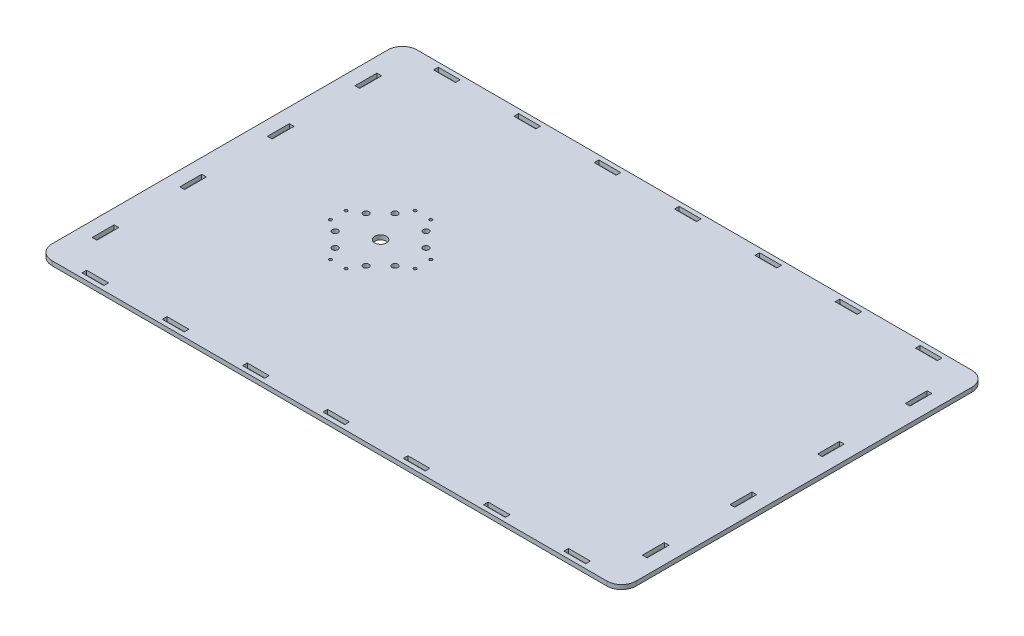
SolidWorks part; units mm, degrees
ref_plane "Front Plane" through (0, 0, 0) normal (0, 0, 1) x (1, 0, 0)
ref_plane "Top Plane" through (0, 0, 0) normal (0, 1, 0) x (1, 0, 0)
ref_plane "Right Plane" through (0, 0, 0) normal (1, 0, 0) x (0, 0, -1)
sketch "Sketch1" plane through (0, 0, 0) normal (0, 1, 0) x (1, 0, 0)
  line L0 (82.5, 3) -> (82.5, 6.2)
  line L1 (0, 0) -> (400, 0)
  line L2 (0, 0) -> (0, 250)
  line L3 (0, 250) -> (400, 250)
  line L4 (400, 0) -> (400, 250)
  line L5 (27.5, 3) -> (42.5, 3)
  line L6 (27.5, 3) -> (27.5, 6.2)
  line L7 (27.5, 6.2) -> (42.5, 6.2)
  line L8 (42.5, 3) -> (42.5, 6.2)
  line L9 (82.5, 3) -> (97.5, 3)
  line L10 (97.5, 3) -> (97.5, 6.2)
  line L11 (82.5, 6.2) -> (97.5, 6.2)
  line L12 (137.5, 3) -> (137.5, 6.2)
  line L13 (137.5, 3) -> (152.5, 3)
  line L14 (152.5, 3) -> (152.5, 6.2)
  line L15 (137.5, 6.2) -> (152.5, 6.2)
  line L16 (192.5, 3) -> (192.5, 6.2)
  line L17 (192.5, 3) -> (207.5, 3)
  line L18 (207.5, 3) -> (207.5, 6.2)
  line L19 (192.5, 6.2) -> (207.5, 6.2)
  line L20 (247.5, 3) -> (247.5, 6.2)
  line L21 (247.5, 3) -> (262.5, 3)
  line L22 (262.5, 3) -> (262.5, 6.2)
  line L23 (247.5, 6.2) -> (262.5, 6.2)
  line L24 (302.5, 3) -> (302.5, 6.2)
  line L25 (302.5, 3) -> (317.5, 3)
  line L26 (317.5, 3) -> (317.5, 6.2)
  line L27 (302.5, 6.2) -> (317.5, 6.2)
  line L28 (357.5, 3) -> (357.5, 6.2)
  line L29 (357.5, 3) -> (372.5, 3)
  line L30 (372.5, 3) -> (372.5, 6.2)
  line L31 (357.5, 6.2) -> (372.5, 6.2)
  line L32 (0, 125) -> (400, 125) construction
  line L33 (357.5, 247) -> (372.5, 247)
  line L34 (372.5, 247) -> (372.5, 243.8)
  line L35 (357.5, 243.8) -> (372.5, 243.8)
  line L36 (357.5, 247) -> (357.5, 243.8)
  line L37 (302.5, 247) -> (317.5, 247)
  line L38 (317.5, 247) -> (317.5, 243.8)
  line L39 (302.5, 243.8) -> (317.5, 243.8)
  line L40 (302.5, 247) -> (302.5, 243.8)
  line L41 (247.5, 247) -> (262.5, 247)
  line L42 (262.5, 247) -> (262.5, 243.8)
  line L43 (247.5, 243.8) -> (262.5, 243.8)
  line L44 (247.5, 247) -> (247.5, 243.8)
  line L45 (192.5, 247) -> (207.5, 247)
  line L46 (207.5, 247) -> (207.5, 243.8)
  line L47 (192.5, 243.8) -> (207.5, 243.8)
  line L48 (192.5, 247) -> (192.5, 243.8)
  line L49 (27.5, 243.8) -> (42.5, 243.8)
  line L50 (42.5, 247) -> (42.5, 243.8)
  line L51 (27.5, 247) -> (42.5, 247)
  line L52 (27.5, 247) -> (27.5, 243.8)
  line L53 (82.5, 247) -> (97.5, 247)
  line L54 (97.5, 247) -> (97.5, 243.8)
  line L55 (82.5, 243.8) -> (97.5, 243.8)
  line L56 (82.5, 247) -> (82.5, 243.8)
  line L57 (137.5, 247) -> (152.5, 247)
  line L58 (152.5, 247) -> (152.5, 243.8)
  line L59 (137.5, 243.8) -> (152.5, 243.8)
  line L60 (137.5, 247) -> (137.5, 243.8)
  line L61 (200, 0) -> (200, 250) construction
  line L62 (10, 102.5) -> (10, 87.5)
  line L63 (10, 42.5) -> (13.2, 42.5)
  line L64 (10, 42.5) -> (10, 27.5)
  line L65 (10, 27.5) -> (13.2, 27.5)
  line L66 (13.2, 42.5) -> (13.2, 27.5)
  line L67 (10, 102.5) -> (13.2, 102.5)
  line L68 (13.2, 102.5) -> (13.2, 87.5)
  line L69 (10, 87.5) -> (13.2, 87.5)
  line L70 (10, 162.5) -> (10, 147.5)
  line L71 (10, 162.5) -> (13.2, 162.5)
  line L72 (13.2, 162.5) -> (13.2, 147.5)
  line L73 (10, 147.5) -> (13.2, 147.5)
  line L74 (10, 222.5) -> (10, 207.5)
  line L75 (10, 222.5) -> (13.2, 222.5)
  line L76 (13.2, 222.5) -> (13.2, 207.5)
  line L77 (10, 207.5) -> (13.2, 207.5)
  line L78 (390, 27.5) -> (386.8, 27.5)
  line L79 (386.8, 42.5) -> (386.8, 27.5)
  line L80 (390, 42.5) -> (386.8, 42.5)
  line L81 (390, 42.5) -> (390, 27.5)
  line L82 (390, 102.5) -> (386.8, 102.5)
  line L83 (386.8, 102.5) -> (386.8, 87.5)
  line L84 (390, 87.5) -> (386.8, 87.5)
  line L85 (390, 102.5) -> (390, 87.5)
  line L86 (390, 162.5) -> (386.8, 162.5)
  line L87 (386.8, 162.5) -> (386.8, 147.5)
  line L88 (390, 147.5) -> (386.8, 147.5)
  line L89 (390, 162.5) -> (390, 147.5)
  line L90 (390, 222.5) -> (386.8, 222.5)
  line L91 (386.8, 222.5) -> (386.8, 207.5)
  line L92 (390, 207.5) -> (386.8, 207.5)
  line L93 (390, 222.5) -> (390, 207.5)
  dimension "D1" = 400
  dimension "D2" = 250
  dimension "D3" = 15
  dimension "D4" = 3.2
  dimension "D5" = 3
  dimension "D6" = 27.5
  dimension "D8" = 40
  dimension "D9" = 15
  dimension "D10" = 3.2
  dimension "D11" = 27.5
  dimension "D12" = 10
  dimension "D14" = 45
  dimension "D7" = 7
  dimension "D13" = 4
extrude "Boss-Extrude2" add sketch "Sketch1" along normal blind 3
fillet "Fillet1" radius 10 4 edges at (400, 1.5, 0) (400, 1.5, -250) (0, 1.5, -250) (0, 1.5, 0)
sketch "Sketch2" plane through (0, 3, 0) normal (0, 1, 0) x (1, 0, 0)
  line L0 (110, 125) -> (75.4669, 159.5331) construction
  line L1 (89.4939, 135.6066) -> (100.9854, 147.0981) construction
  line L2 (110, 125) -> (110, 174.7752) construction
  line L3 (110, 174.7752) -> (110, 125) construction
  line L4 (110, 125) -> (38.4266, 125) construction
  line L5 (38.4266, 125) -> (110, 125) construction
  line L6 (0, 240) -> (0, 10) construction
  circle A3 centre (110, 125) radius 4
  circle A4 centre (104.62, 154) radius 1
  circle A5 centre (115.38, 154) radius 1
  circle A6 centre (99.3934, 145.5061) radius 2
  circle A7 centre (89.4939, 135.6066) radius 2
  circle A8 centre (120.6066, 145.5061) radius 2
  circle A9 centre (130.5061, 135.6066) radius 2
  circle A10 centre (139, 130.38) radius 1
  circle A11 centre (139, 119.62) radius 1
  circle A12 centre (110, 125) radius 4
  circle A13 centre (130.5061, 114.3934) radius 2
  circle A14 centre (120.6066, 104.4939) radius 2
  circle A15 centre (115.38, 96) radius 1
  circle A16 centre (104.62, 96) radius 1
  circle A17 centre (110, 125) radius 4
  circle A18 centre (99.3934, 104.4939) radius 2
  circle A19 centre (89.4939, 114.3934) radius 2
  circle A20 centre (81, 119.62) radius 1
  circle A21 centre (81, 130.38) radius 1
  circle A22 centre (110, 125) radius 4
  point P8 (110, 154)
  point P21 (0, 125)
  point P47 (110, 125)
  dimension "D1" = 8
  dimension "D2" = 45
  dimension "D4" = 4
  dimension "D5" = 5.38
  dimension "D6" = 10.76
  dimension "D7" = 29
  dimension "D3" = 2
  dimension "D9" = 7
  dimension "D8" = 7
  dimension "D10" = 22
  dimension "D11" = 110
  dimension "D12" = 4
extrude "Cut-Extrude1" cut sketch "Sketch2" against normal through all contours A7 | A8 | A9 | A18 | A14 | A19 | A20 | A3 | A21 | A6 | A4 | A5 | A10 | A11 | A13 | A15 | A16
